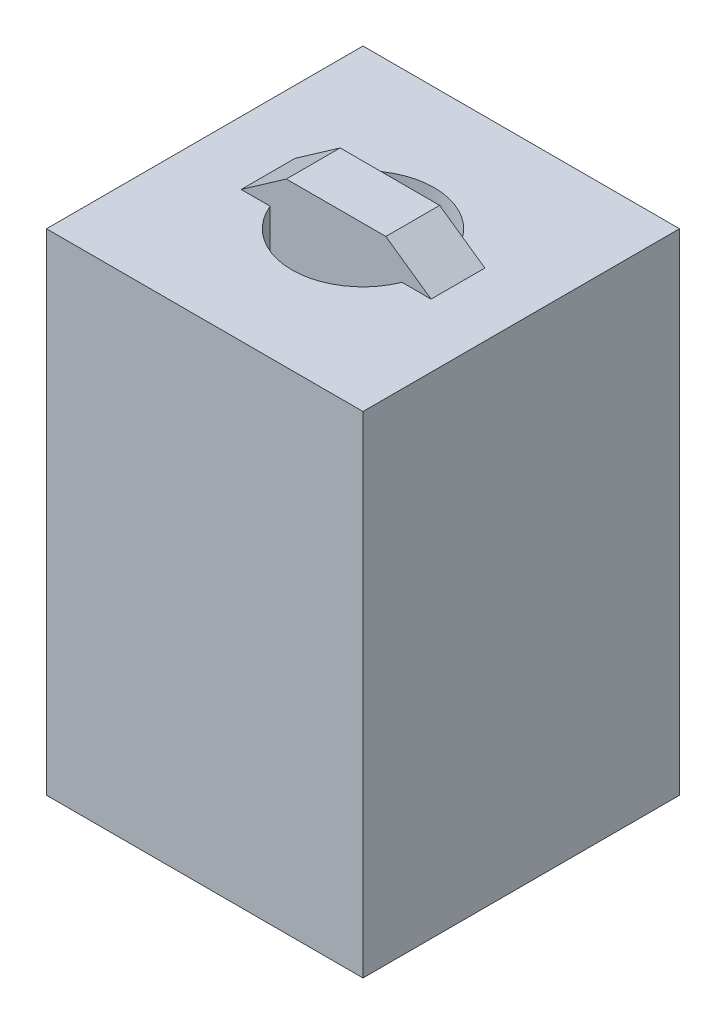
SolidWorks part; units mm, degrees
ref_plane "Front Plane" through (0, 0, 0) normal (0, 0, 1) x (1, 0, 0)
ref_plane "Top Plane" through (0, 0, 0) normal (0, 1, 0) x (1, 0, 0)
ref_plane "Right Plane" through (0, 0, 0) normal (1, 0, 0) x (0, 0, -1)
sketch "Sketch1" plane through (0, 0, 0) normal (0, 1, 0) x (1, 0, 0)
  circle A0 centre (0, 0) radius 12.7
  dimension "D1" = 25.4
extrude "Boss-Extrude1" add sketch "Sketch1" along normal blind 38.1
sketch "Sketch2" plane through (0, 38.1, 0) normal (0, 1, 0) x (1, 0, 0)
  circle A0 centre (0, 0) radius 5.715
  dimension "D1" = 11.43
extrude "Cut-Extrude1" cut sketch "Sketch2" against normal through all
sketch "Sketch3" plane through (0, 0, 0) normal (0, -1, 0) x (1, 0, 0)
  circle A0 centre (0, 0) radius 9.3345
  dimension "D1" = 18.669
extrude "Cut-Extrude2" cut sketch "Sketch3" against normal blind 12.7
sketch "Sketch4" plane through (0, 38.1, 0) normal (0, 1, 0) x (1, 0, 0)
  circle A0 centre (0, 0) radius 5.715 construction
  circle A1 centre (0, 0) radius 12.7
  circle A2 centre (0, 0) radius 12.7
  circle A3 centre (0, 0) radius 5.715
  dimension "D1" = 0
extrude "Boss-Extrude2" add sketch "Sketch4" along normal blind 1.27
sketch "Sketch5" plane through (0, 39.37, 0) normal (0, 1, 0) x (1, 0, 0)
  line L1 (5.715, 2.159) -> (-5.715, 2.159)
  line L2 (5.715, 2.159) -> (5.715, -2.159)
  line L3 (5.715, -2.159) -> (-5.715, -2.159)
  line L4 (-5.715, 2.159) -> (-5.715, -2.159)
  line L5 (5.715, 2.159) -> (-5.715, -2.159) construction
  line L6 (5.715, -2.159) -> (-5.715, 2.159) construction
  circle A0 centre (0, 0) radius 5.715 construction
  point P0 (0, 0)
  dimension "D1" = 4.318
extrude "Boss-Extrude3" add sketch "Sketch5" against normal blind 6.35
sketch "Sketch6" plane through (0, 0, -2.159) normal (0, 0, -1) x (-1, 0, 0)
  line L1 (12.7, 39.37) -> (-12.7, 39.37) construction
  line L3 (7.62, 39.37) -> (-7.62, 39.37)
  line L4 (0, 44.45) -> (0, 0) construction
  line L5 (5.2915, 39.37) -> (5.2915, 40.9581) construction
  line L6 (-7.62, 39.37) -> (-3.9925, 41.91)
  line L7 (-3.9925, 41.91) -> (3.9925, 41.91)
  line L8 (3.9925, 41.91) -> (7.62, 39.37)
  dimension "D1" = 35
  dimension "D2" = 15.24
  dimension "D3" = 1.5881
  dimension "D4" = 2.54
extrude "Boss-Extrude4" add sketch "Sketch6" against normal up to surface (4.318 mm away) up to face at (0, 36.195, 2.159)
sketch "Sketch7" plane through (0, 39.37, 0) normal (0, 1, 0) x (1, 0, 0)
  line L0 (-12.7, 0) -> (-12.7, -12.7)
  line L1 (-12.7, -12.7) -> (12.7, -12.7)
  line L2 (12.7, -12.7) -> (12.7, 0)
  line L3 (-12.7, 0) -> (-12.7, 12.7)
  line L4 (-12.7, 12.7) -> (12.7, 12.7)
  line L5 (12.7, 12.7) -> (12.7, 0)
  circle A0 centre (0, 0) radius 12.7 construction
  arc A1 (12.7, 0) -> (-12.7, 0) centre (0, 0) cw
  arc A2 (-12.7, 0) -> (12.7, 0) centre (0, 0) cw
  point P0 (-12.7, 12.7)
  circle M1 centre (0, 0) radius 12.7
extrude "Boss-Extrude5" add sketch "Sketch7" against normal up to surface (39.37 mm away) contours L1 L2 M1 | L0 L1 M1 | L4 L3 M1 | L5 L4 M1 up to face at (0, 0, -9.3345)
